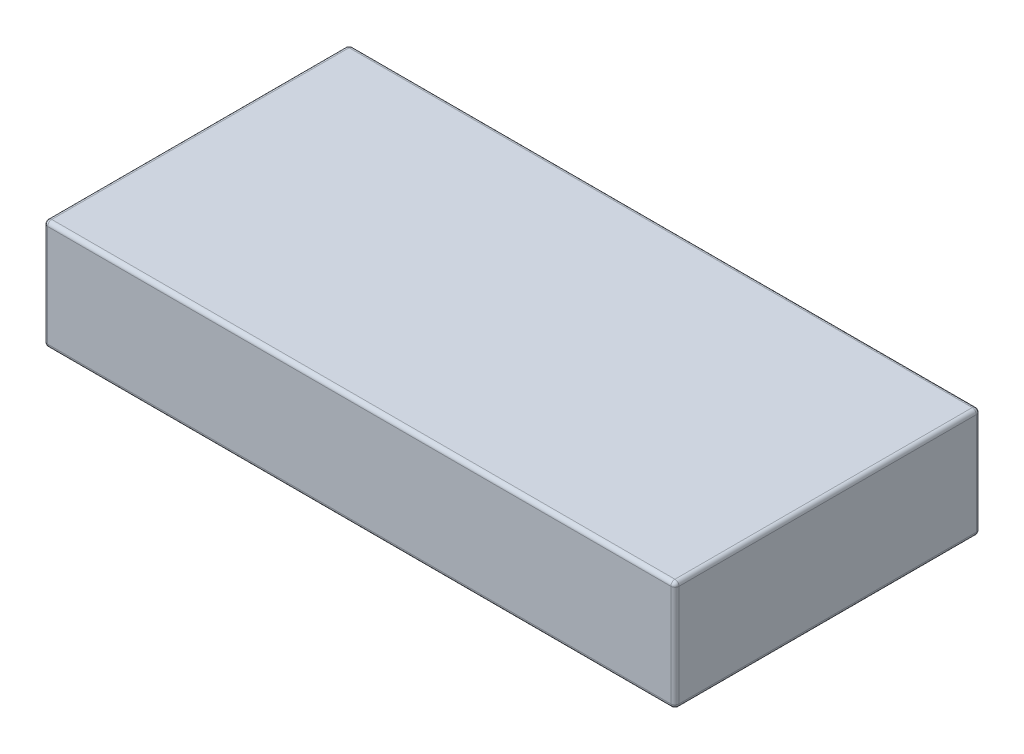
SolidWorks part; units mm, degrees
ref_plane "Front Plane" through (0, 0, 0) normal (0, 0, 1) x (1, 0, 0)
ref_plane "Top Plane" through (0, 0, 0) normal (0, 1, 0) x (1, 0, 0)
ref_plane "Right Plane" through (0, 0, 0) normal (1, 0, 0) x (0, 0, -1)
sketch "Sketch1" plane through (0, 0, 0) normal (0, 1, 0) x (1, 0, 0)
  line L1 (-77.5, 37.5) -> (77.5, 37.5)
  line L2 (-77.5, 37.5) -> (-77.5, -37.5)
  line L3 (-77.5, -37.5) -> (77.5, -37.5)
  line L4 (77.5, 37.5) -> (77.5, -37.5)
  line L5 (-77.5, 37.5) -> (77.5, -37.5) construction
  line L6 (-77.5, -37.5) -> (77.5, 37.5) construction
  point P0 (0, 0)
  dimension "D1" = 75
  dimension "D2" = 155
extrude "Boss-Extrude1" add sketch "Sketch1" along normal blind 27
fillet "Fillet1" radius 1 12 edges at (77.5, 13.5, -37.5) (-77.5, 13.5, -37.5) (-77.5, 13.5, 37.5) (77.5, 13.5, 37.5) (0, 27, 37.5) (-77.5, 27, 0) (0, 27, -37.5) (77.5, 27, 0) (0, 0, -37.5) (-77.5, 0, 0) (0, 0, 37.5) (77.5, 0, 0)
